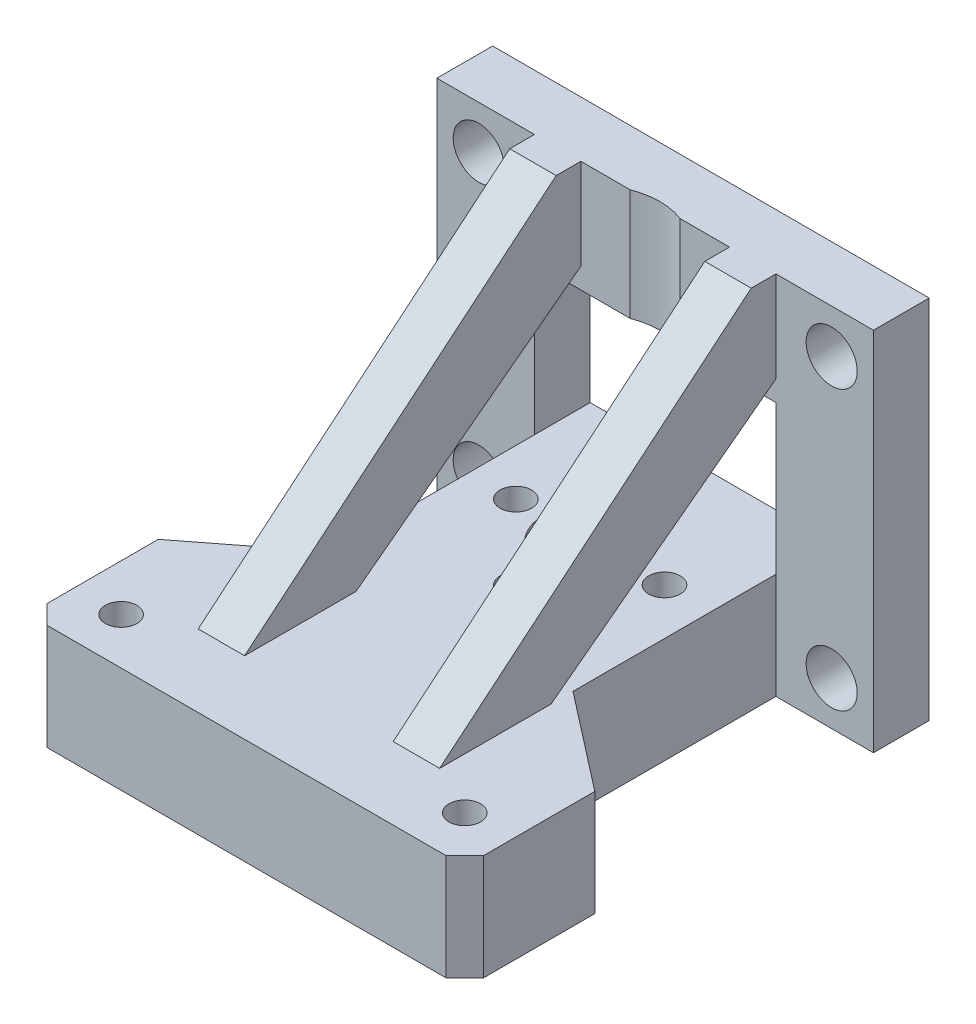
SolidWorks part; units mm, degrees
ref_plane "Front Plane" through (0, 0, 0) normal (0, 0, 1) x (1, 0, 0)
ref_plane "Top Plane" through (0, 0, 0) normal (0, 1, 0) x (1, 0, 0)
ref_plane "Right Plane" through (0, 0, 0) normal (1, 0, 0) x (0, 0, -1)
sketch "Sketch1" plane through (0, 0, 0) normal (0, 0, 1) x (1, 0, 0)
  line L1 (-23.5, -19.7) -> (23.5, -19.7)
  line L2 (-23.5, -19.7) -> (-23.5, 19.7)
  line L3 (-23.5, 19.7) -> (23.5, 19.7)
  line L4 (23.5, -19.7) -> (23.5, 19.7)
  line L5 (-23.5, -19.7) -> (23.5, 19.7) construction
  line L6 (-23.5, 19.7) -> (23.5, -19.7) construction
  point P0 (0, 0)
extrude "Boss-Extrude1" add sketch "Sketch1" along normal blind 50
sketch "Sketch2" plane through (0, 0, 0) normal (0, 0, -1) x (-1, 0, 0)
  line L0 (-23.5, 19.7) -> (23.5, 19.7) construction
  point P0 (19, 15)
  point P1 (-19, 15)
  point P2 (-19, -15)
  point P3 (19, -15)
sketch "Sketch3" plane through (0, 19.7, 0) normal (0, 1, 0) x (1, 0, 0)
  line L0 (0, 0) -> (0, -50) construction
  line L1 (23.5, -50) -> (23.5, 0) construction
  line L2 (23.5, -6) -> (13, -6)
  line L3 (13, -6) -> (13, -36)
  line L4 (13, -36) -> (23.5, -36)
  line L5 (23.5, -36) -> (23.5, -6)
  line L6 (23.5, 0) -> (-23.5, 0) construction
  line L7 (23.5, -50) -> (-23.5, -50) construction
  line L8 (-23.5, -36) -> (-23.5, -6)
  line L9 (-13, -36) -> (-23.5, -36)
  line L10 (-13, -6) -> (-13, -36)
  line L11 (-23.5, -6) -> (-13, -6)
extrude "Cut-Extrude1" cut sketch "Sketch3" against normal blind 50
sketch "Sketch19" plane through (0, -19.7, 0) normal (0, -1, 0) x (1, 0, 0)
  circle A0 centre (0, 13) radius 5
extrude "Cut-Extrude6" cut sketch "Sketch19" against normal through all
hole_wizard "M5 Clearance Hole1" positions "Sketch23" profile "Sketch24" hole size "M5" standard "ISO"
sketch "Sketch23" plane through (0, 0, 0) normal (0, 0, -1) x (-1, 0, 0)
  point P0 (-19, -15)
  point P3 (-19, 15)
  point P6 (19, 15)
  point P9 (19, -15)
sketch "Sketch24" plane through (19, -15, 0) normal (1, 0, 0) x (0, 1, 0)
  line L0 (0, 0) -> (0, 6)
  line L1 (0, 6) -> (2.75, 6)
  line L2 (2.75, 6) -> (2.75, 0)
  line L5 (2.75, 0) -> (0, 0)
  line L11 (0, -6.35) -> (0, 107.95) construction
  dimension "Thru Hole Dia." = 5.5
  dimension "Thru Hole Depth" = 6
sketch "Sketch25" plane through (0, 19.7, 0) normal (0, 1, 0) x (1, 0, 0)
  circle A0 centre (0, -13) radius 7.5
  dimension "D1" = 15
extrude "Cut-Extrude7" cut sketch "Sketch25" against normal blind 28 contours A0
sketch "Sketch26" plane through (0, 19.7, 0) normal (0, 1, 0) x (1, 0, 0)
  line L0 (13, -6) -> (13, -36)
  line L1 (13, -36) -> (23.5, -36)
  line L2 (23.5, -50) -> (23.5, -36) construction
  line L3 (13, -36) -> (23.5, -36) construction
  line L4 (23.5, -36) -> (23.5, -50)
  line L5 (23.5, -50) -> (-23.5, -50)
  line L6 (-23.5, -50) -> (-23.5, -36)
  line L7 (-23.5, -36) -> (-13, -36)
  line L8 (-13, -36) -> (-13, -6)
  line L9 (-13, -6) -> (13, -6)
extrude "Cut-Extrude8" cut sketch "Sketch26" against normal blind 28
sketch "Sketch27" plane through (0, 0, 6) normal (0, 0, 1) x (1, 0, 0)
  line L0 (13, -8.3) -> (-13, -8.3)
  line L1 (13, -8.3) -> (13, 7.7)
  line L2 (-13, -8.3) -> (-13, 7.7)
  line L3 (13, 7.7) -> (-13, 7.7)
extrude "Cut-Extrude9" cut sketch "Sketch27" against normal blind 28
sketch "Sketch28" plane through (0, -19.7, 0) normal (0, -1, 0) x (1, 0, 0)
  line L0 (0, 13) -> (0, 21) construction
  line L1 (0, 21) -> (0, 13) construction
  line L2 (0, 13) -> (8, 13) construction
  line L3 (0, 13) -> (0, 5) construction
  line L4 (0, 5) -> (0, 13) construction
  line L5 (0, 13) -> (-8, 13) construction
  line L6 (-23.5, 50) -> (-23.5, 36) construction
  line L7 (23.5, 50) -> (23.5, 36) construction
  line L10 (-23.5, 50) -> (23.5, 50) construction
  circle A0 centre (0, 21) radius 1.7
  circle A1 centre (8, 13) radius 1.7
  circle A2 centre (0, 5) radius 1.7
  circle A3 centre (-8, 13) radius 1.7
  circle A4 centre (-18.5, 45) radius 1.7
  circle A5 centre (18.5, 45) radius 1.7
  dimension "D1" = 5
  dimension "D2" = 5
  dimension "D3" = 5
  dimension "D4" = 5
extrude "Cut-Extrude10" cut sketch "Sketch28" against normal up to next
sketch "Sketch29" plane through (13, 0, 0) normal (1, 0, 0) x (0, 0, -1)
  line L0 (-42.2057, -8.3) -> (-30.2057, -8.3)
  line L1 (-36, -8.3) -> (-6, -8.3) construction
  line L2 (-30.2057, -8.3) -> (-6, 9.9198)
  line L3 (-6, 9.9198) -> (-6, 19.7)
  line L4 (-8.6595, 19.7) -> (-42.2057, -8.3)
  line L5 (-6, 19.7) -> (-8.6595, 19.7)
extrude "Boss-Extrude2" add sketch "Sketch29" against normal blind 26
sketch "Sketch30" plane through (0, 19.7, 0) normal (0, 1, 0) x (1, 0, 0)
  line L0 (13, -6) -> (8, -6) construction
  line L1 (-13, -6) -> (-8, -6) construction
  line L2 (8, -6) -> (-8, -6)
  line L3 (8, -6) -> (8, -47.7367)
  line L4 (-8, -6) -> (-8, -47.7367)
  line L5 (8, -47.7367) -> (-8, -47.7367)
extrude "Cut-Extrude11" cut sketch "Sketch30" against normal blind 28
sketch "Sketch31" plane through (0, -19.7, 0) normal (0, -1, 0) x (1, 0, 0)
  line L0 (-23.5, 36) -> (-13, 36)
  line L1 (-13, 36) -> (-13, 27.8469)
  line L2 (-13, 36) -> (-13, 6) construction
  line L3 (-13, 27.8469) -> (-23.5, 36)
  line L4 (13, 36) -> (13, 27.8469)
  line L5 (13, 6) -> (13, 36) construction
  line L6 (13, 27.8469) -> (23.5, 36)
  line L7 (23.5, 36) -> (13, 36)
extrude "Boss-Extrude3" add sketch "Sketch31" against normal up to vertex (11.4 mm away) up to point (23.5, -8.3, 36)
chamfer "Chamfer1" distance 2 angle 45 2 edges at (-23.5, -14, 50) (23.5, -14, 50)
